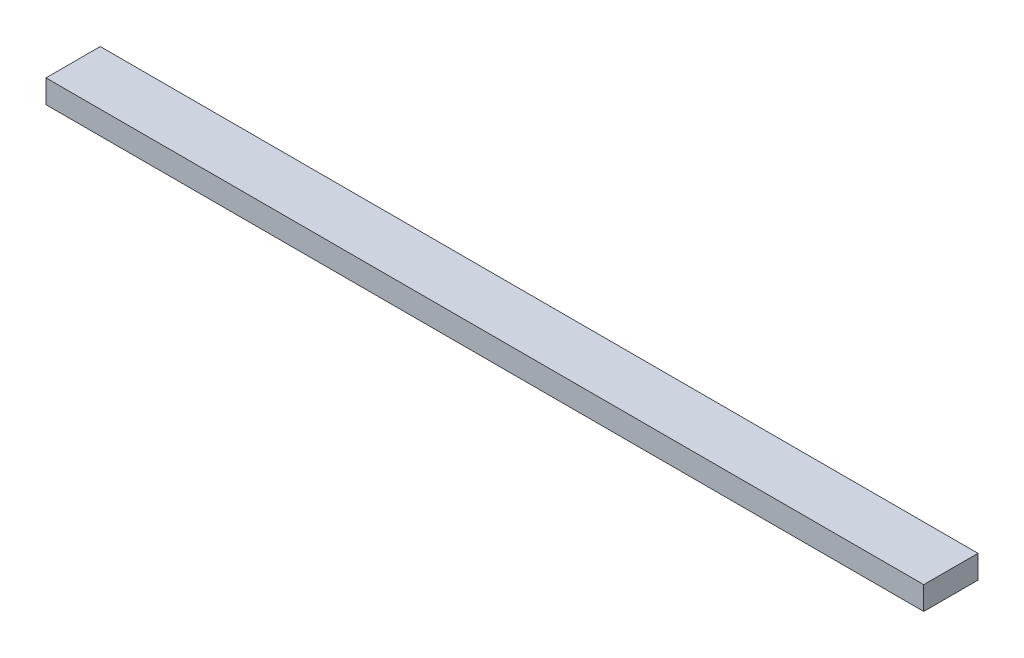
SolidWorks part; units mm, degrees
material "Pine"
ref_plane "Front Plane" through (0, 0, 0) normal (0, 0, 1) x (1, 0, 0)
ref_plane "Top Plane" through (0, 0, 0) normal (0, 1, 0) x (1, 0, 0)
ref_plane "Right Plane" through (0, 0, 0) normal (1, 0, 0) x (0, 0, -1)
sketch "Sketch1" plane through (0, 0, 0) normal (1, 0, 0) x (0, 0, -1)
  line L1 (0, 0) -> (88.9, 0)
  line L2 (0, 0) -> (0, 38.1)
  line L3 (0, 38.1) -> (88.9, 38.1)
  line L4 (88.9, 0) -> (88.9, 38.1)
  dimension "D1" = 38.1
  dimension "D2" = 88.9
extrude "Boss-Extrude1" add sketch "Sketch1" along normal blind 1438.275
